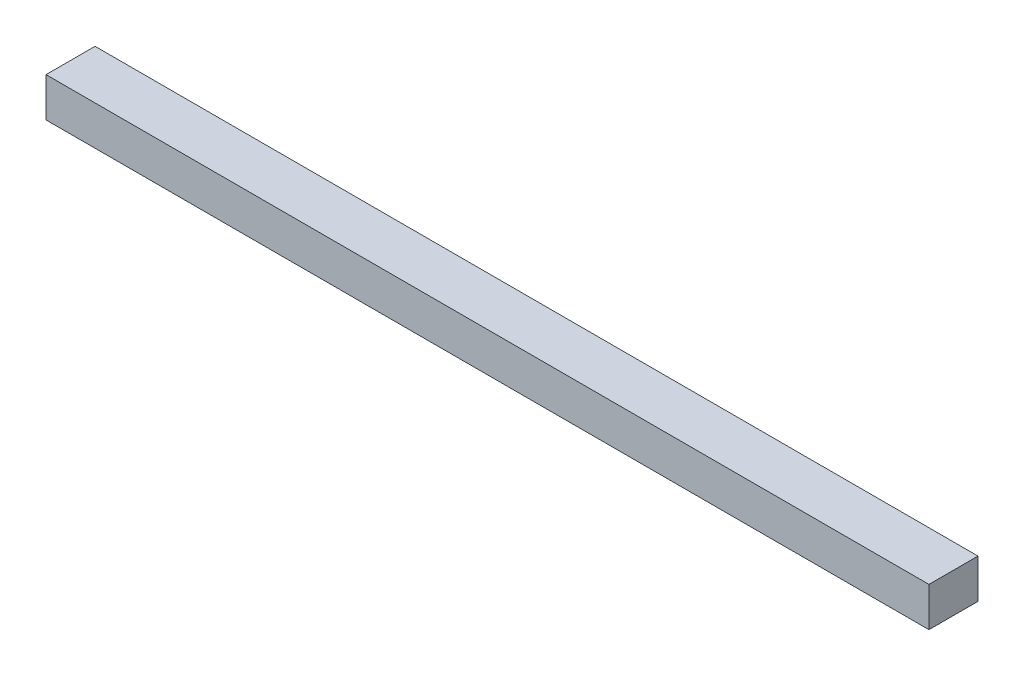
SolidWorks part; units mm, degrees
ref_plane "前视基准面" through (0, 0, 0) normal (0, 0, 1) x (1, 0, 0)
ref_plane "上视基准面" through (0, 0, 0) normal (0, 1, 0) x (1, 0, 0)
ref_plane "右视基准面" through (0, 0, 0) normal (1, 0, 0) x (0, 0, -1)
sketch "草图1" plane through (0, 0, 0) normal (0, 1, 0) x (1, 0, 0)
  line L1 (-51.0642, 30.9728) -> (128.9358, 30.9728)
  line L2 (-51.0642, 30.9728) -> (-51.0642, 20.9728)
  line L3 (-51.0642, 20.9728) -> (128.9358, 20.9728)
  line L4 (128.9358, 30.9728) -> (128.9358, 20.9728)
  dimension "D1" = 180
  dimension "D2" = 10
extrude "凸台-拉伸1" add sketch "草图1" along normal blind 8
